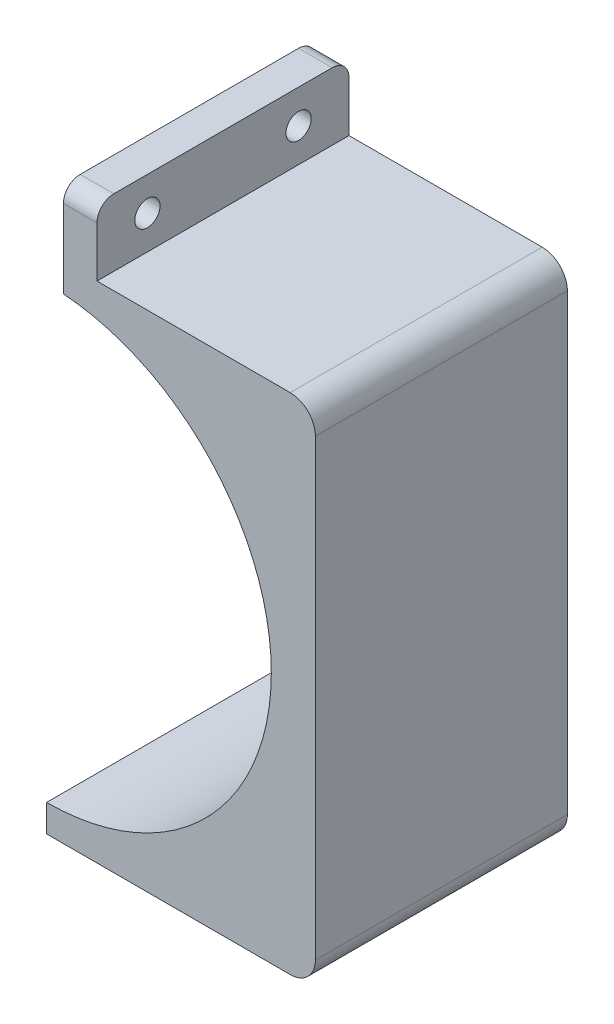
SolidWorks part; units mm, degrees
ref_plane "前视基准面" through (0, 0, 0) normal (0, 0, 1) x (1, 0, 0)
ref_plane "上视基准面" through (0, 0, 0) normal (0, 1, 0) x (1, 0, 0)
ref_plane "右视基准面" through (0, 0, 0) normal (1, 0, 0) x (0, 0, -1)
sketch "草图1" plane through (0, 0, 0) normal (0, 0, 1) x (1, 0, 0)
  line L0 (0, 0) -> (0, 30) construction
  line L1 (-32, 30) -> (-6, 30)
  line L2 (-32, 30) -> (-32, -30)
  line L3 (-32, -30) -> (32, -30)
  line L4 (32, 30) -> (32, -30)
  line L5 (-32, 30) -> (32, -30) construction
  line L6 (-32, -30) -> (32, 30) construction
  line L7 (-6, 30) -> (-6, 38)
  line L8 (-6, 38) -> (6, 38) construction
  line L9 (6, 38) -> (6, 30)
  line L11 (6, 30) -> (32, 30)
  line L13 (2, 38) -> (2, 28.6593)
  line L14 (-2, 28.6593) -> (-2, 38)
  line L16 (-6, 38) -> (-2, 38)
  line L17 (2, 38) -> (6, 38)
  line L18 (-2, 28.6593) -> (-2, 26.6751)
  line L19 (2, 28.6593) -> (2, 26.6751)
  arc A0 (2, 26.6751) -> (-2, 26.6751) centre (0, 0) ccw construction
  arc A1 (-2, 26.6751) -> (2, 26.6751) centre (0, 0) ccw
  point P0 (0, 0)
  point P7 (0, -30)
  point P16 (2, 28.6593)
  point P21 (0, 38)
  point P22 (-2, 28.6593)
  point P23 (0, 0)
  point P24 (0, 0)
  point P25 (0, 0)
  dimension "D3" = 53.5
  dimension "D1" = 64
  dimension "D2" = 60
  dimension "D4" = 6
  dimension "D5" = 6
  dimension "D6" = 8
  dimension "D7" = 4
  dimension "D8" = 4
extrude "凸台-拉伸1" add sketch "草图1" along normal blind 30
fillet "圆角1" radius 3 4 edges at (32, -30, 15) (32, 30, 15) (-32, -30, 15) (-32, 30, 15)
ref_plane "基准面1" through (0, 0, 0) normal (1, 0, 0) x (0, 0, -1)
sketch "草图3" plane through (0, -30, 0) normal (0, -1, 0) x (1, 0, 0)
  line L0 (-29, 30) -> (29, 30) construction
  line L1 (29, 0) -> (29, 30) construction
  line L2 (19, 24) -> (19, 6) construction
  line L3 (-29, 0) -> (29, 0) construction
  circle A0 centre (19, 24) radius 2
  circle A1 centre (19, 6) radius 2
  dimension "D1" = 4
  dimension "D3" = 6
  dimension "D4" = 10
  dimension "D5" = 6
extrude "切除-拉伸1" cut sketch "草图3" against normal blind 7
sketch "草图4" plane through (6, 0, 0) normal (1, 0, 0) x (0, 0, -1)
  line L0 (-24, 34) -> (-6, 34) construction
  line L2 (-30, 38) -> (0, 38) construction
  line L3 (-30, 30) -> (-30, 38) construction
  line L4 (0, 30) -> (0, 38) construction
  circle A0 centre (-24, 34) radius 1.5
  circle A1 centre (-6, 34) radius 1.5
  dimension "D1" = 3
  dimension "D2" = 3
  dimension "D3" = 4
  dimension "D4" = 6
  dimension "D5" = 6
extrude "切除-拉伸2" cut sketch "草图4" along direction (1, 0, 0) on the side against the normal through all
sketch "草图5" plane through (0, 0, 0) normal (1, 0, 0) x (0, 0, -1)
  line L1 (-118.779, 138.5944) -> (23.01, 138.5944)
  line L2 (-118.779, 138.5944) -> (-118.779, -38.8542)
  line L3 (-118.779, -38.8542) -> (23.01, -38.8542)
  line L4 (23.01, 138.5944) -> (23.01, -38.8542)
  line L5 (-118.779, 138.5944) -> (23.01, -38.8542) construction
  line L6 (-118.779, -38.8542) -> (23.01, 138.5944) construction
  point P0 (-47.8845, 49.8701)
extrude "切除-拉伸3" cut sketch "草图5" against normal through all
fillet "圆角2" radius 2 2 edges at (4, 38, 0) (4, 38, 30)
